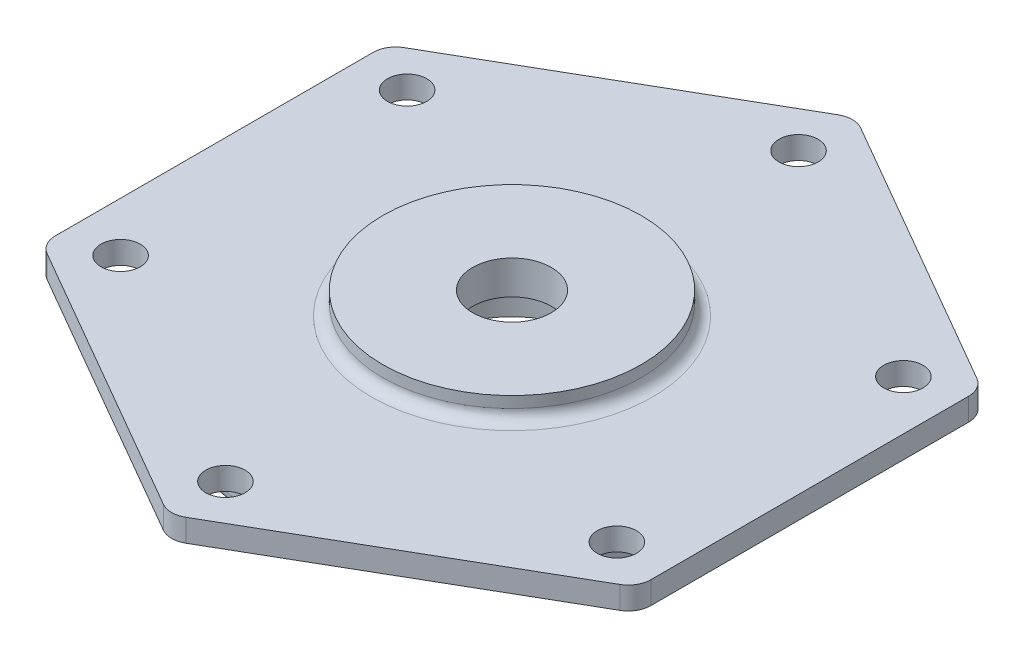
SolidWorks part; units mm, degrees
ref_plane "Front Plane" through (0, 0, 0) normal (0, 0, 1) x (1, 0, 0)
ref_plane "Top Plane" through (0, 0, 0) normal (0, 1, 0) x (1, 0, 0)
ref_plane "Right Plane" through (0, 0, 0) normal (1, 0, 0) x (0, 0, -1)
sketch "Sketch1" plane through (0, 0, 0) normal (0, 1, 0) x (1, 0, 0)
  line L1 (2, -60.0444) -> (51, -31.7543)
  line L2 (53, -28.2902) -> (53, 28.2902)
  line L3 (51, 31.7543) -> (2, 60.0444)
  line L4 (-2, 60.0444) -> (-51, 31.7543)
  line L5 (-53, 28.2902) -> (-53, -28.2902)
  line L6 (-51, -31.7543) -> (-2, -60.0444)
  circle A0 centre (0, 0) radius 53 construction
  arc A1 (-53, -28.2902) -> (-51, -31.7543) centre (-49, -28.2902) ccw
  arc A2 (-51, 31.7543) -> (-53, 28.2902) centre (-49, 28.2902) ccw
  arc A3 (2, 60.0444) -> (-2, 60.0444) centre (0, 56.5803) ccw
  arc A4 (53, 28.2902) -> (51, 31.7543) centre (49, 28.2902) ccw
  arc A5 (51, -31.7543) -> (53, -28.2902) centre (49, -28.2902) ccw
  arc A6 (2, -60.0444) -> (-2, -60.0444) centre (0, -56.5803) cw
  point P16 (0, 61.1991)
  dimension "D2" = 4
  dimension "D1" = 106
extrude "Boss-Extrude1" add sketch "Sketch1" along normal blind 4
sketch "Sketch2" plane through (0, 4, 0) normal (0, 1, 0) x (1, 0, 0)
  circle A0 centre (0, 0) radius 23
  dimension "D1" = 46
extrude "Boss-Extrude2" add sketch "Sketch2" along normal blind 4
sketch "Sketch3" plane through (0, 0, 0) normal (0, -1, 0) x (1, 0, 0)
  circle A0 centre (0, 0) radius 45
  dimension "D1" = 90
extrude "Boss-Extrude3" add sketch "Sketch3" along normal blind 6
sketch "Sketch4" plane through (0, -6, 0) normal (0, -1, 0) x (1, 0, 0)
  circle A0 centre (0, 0) radius 40
  circle A1 centre (1.216, 0) radius 19
  dimension "D1" = 38
  dimension "D2" = 80
extrude "Cut-Extrude1" cut sketch "Sketch4" against normal blind 6
sketch "Sketch5" plane through (0, -6, 0) normal (0, -1, 0) x (1, 0, 0)
  circle A0 centre (0, 0) radius 14
  dimension "D1" = 28
extrude "Cut-Extrude2" cut sketch "Sketch5" against normal blind 8
sketch "Sketch6" plane through (0, 2, 0) normal (0, -1, 0) x (1, 0, 0)
  circle A0 centre (0, 0) radius 7
  dimension "D1" = 14
extrude "Cut-Extrude3" cut sketch "Sketch6" against normal through all
fillet "Fillet1" radius 2 1 edges at (1.216, -6, -19)
fillet "Fillet2" radius 2 1 edges at (0, 4, 23)
fillet "Fillet3" radius 2 1 edges at (0, -6, -45)
sketch "Sketch7" plane through (0, 4, 0) normal (0, 1, 0) x (1, 0, 0)
  circle A0 centre (0, 0) radius 51 construction
  circle A1 centre (0, 51) radius 3.5
  circle A2 centre (44.1673, 25.5) radius 3.5
  circle A3 centre (44.1673, -25.5) radius 3.5
  circle A4 centre (0, -51) radius 3.5
  circle A5 centre (-44.1673, -25.5) radius 3.5
  circle A6 centre (-44.1673, 25.5) radius 3.5
  point P18 (0, 0)
  dimension "D1" = 102
  dimension "D2" = 7
  dimension "D3" = 6
extrude "Cut-Extrude4" cut sketch "Sketch7" against normal through all
